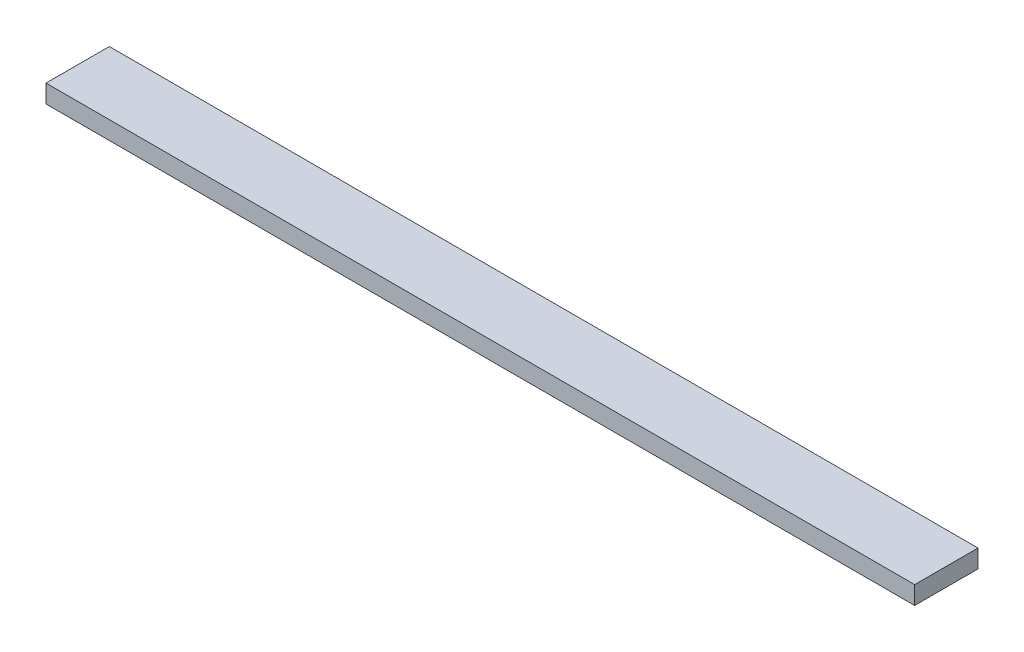
SolidWorks part; units mm, degrees
material "Acrylic (Medium-high impact)"
ref_plane "Front Plane" through (0, 0, 0) normal (0, 0, 1) x (1, 0, 0)
ref_plane "Top Plane" through (0, 0, 0) normal (0, 1, 0) x (1, 0, 0)
ref_plane "Right Plane" through (0, 0, 0) normal (1, 0, 0) x (0, 0, -1)
sketch "Sketch1" plane through (0, 0, 0) normal (0, 1, 0) x (1, 0, 0)
  line L13 (-152.4, -11.1125) -> (152.4, -11.1125)
  line L14 (-152.4, -11.1125) -> (-152.4, 11.1125)
  line L15 (-152.4, 11.1125) -> (152.4, 11.1125)
  line L16 (152.4, -11.1125) -> (152.4, 11.1125)
  line L17 (-152.4, -11.1125) -> (152.4, 11.1125) construction
  line L18 (-152.4, 11.1125) -> (152.4, -11.1125) construction
  point P0 (0, 0)
  dimension "D1" = 304.8
  dimension "D2" = 22.225
extrude "Boss-Extrude1" add sketch "Sketch1" along normal blind 6.35
